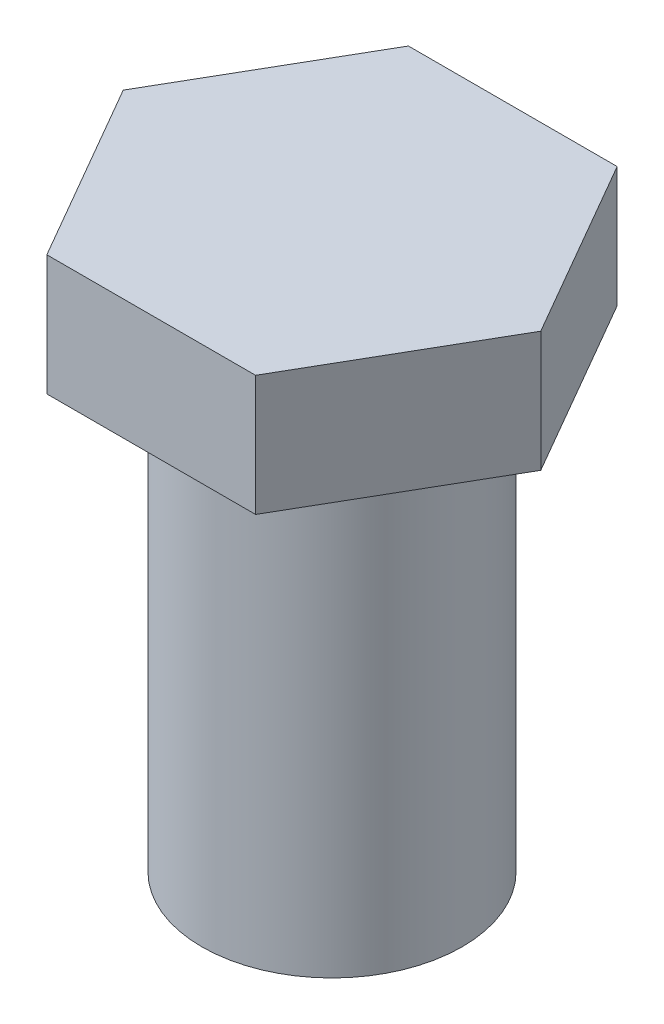
SolidWorks part; units mm, degrees
ref_plane "Front Plane" through (0, 0, 0) normal (0, 0, 1) x (1, 0, 0)
ref_plane "Top Plane" through (0, 0, 0) normal (0, 1, 0) x (1, 0, 0)
ref_plane "Right Plane" through (0, 0, 0) normal (1, 0, 0) x (0, 0, -1)
sketch "Sketch1" plane through (0, 0, 0) normal (0, 1, 0) x (1, 0, 0)
  circle A0 centre (0, 0) radius 2.7432
  dimension "D1" = 5.4864
extrude "Boss-Extrude1" add sketch "Sketch1" against normal blind 9.525
sketch "Sketch2" plane through (0, 0, 0) normal (0, 1, 0) x (1, 0, 0)
  line L1 (4.3994, 0) -> (2.1997, 3.81)
  line L2 (2.1997, 3.81) -> (-2.1997, 3.81)
  line L3 (-2.1997, 3.81) -> (-4.3994, 0)
  line L4 (-4.3994, 0) -> (-2.1997, -3.81)
  line L5 (-2.1997, -3.81) -> (2.1997, -3.81)
  line L6 (2.1997, -3.81) -> (4.3994, 0)
  circle A0 centre (0, 0) radius 3.81 construction
  dimension "D1" = 7.62
extrude "Boss-Extrude2" add sketch "Sketch2" along normal blind 2.54
